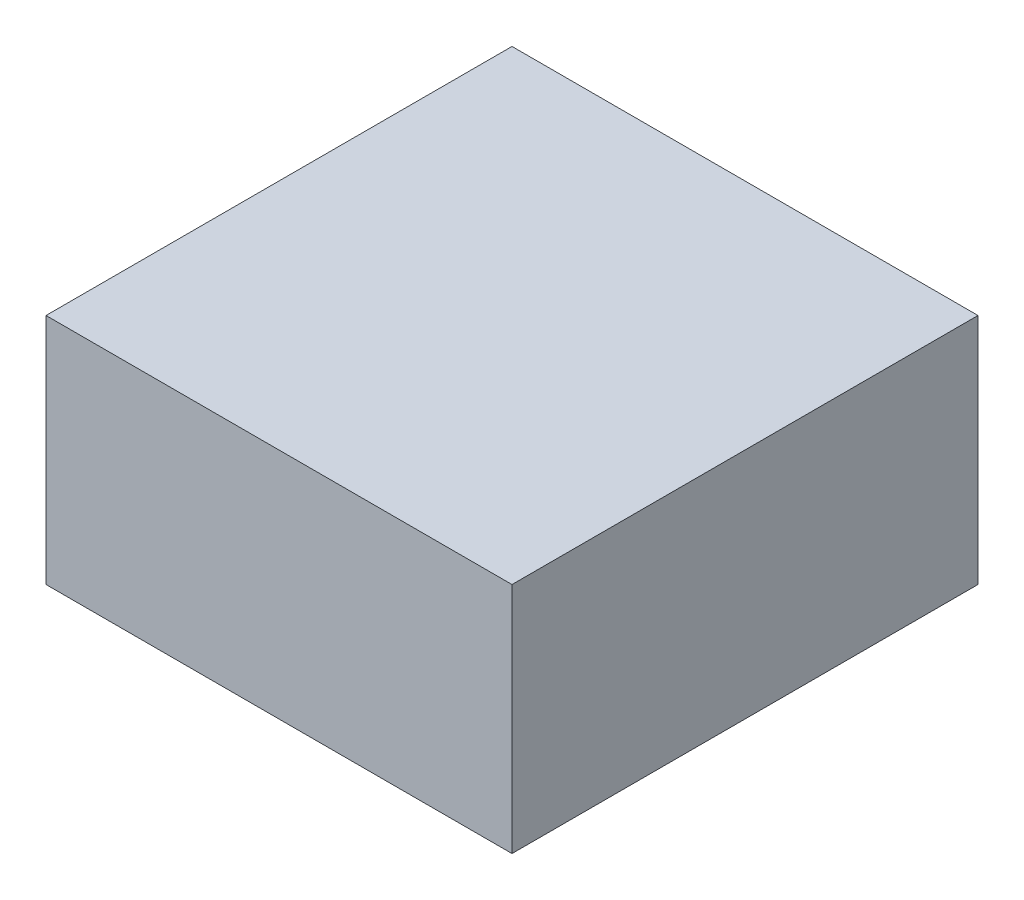
SolidWorks part; units mm, degrees
ref_plane "Front Plane" through (0, 0, 0) normal (0, 0, 1) x (1, 0, 0)
ref_plane "Top Plane" through (0, 0, 0) normal (0, 1, 0) x (1, 0, 0)
ref_plane "Right Plane" through (0, 0, 0) normal (1, 0, 0) x (0, 0, -1)
sketch "Sketch1" plane through (0, 0, 0) normal (0, 1, 0) x (1, 0, 0)
  line L1 (-50, 100) -> (50, 100)
  line L2 (-50, 100) -> (-50, 0)
  line L3 (-50, 0) -> (50, 0)
  line L4 (50, 100) -> (50, 0)
  point P4 (0, 0)
  dimension "D1" = 100
extrude "Boss-Extrude1" add sketch "Sketch1" along normal blind 50 contours L2 L3 L4 L1
